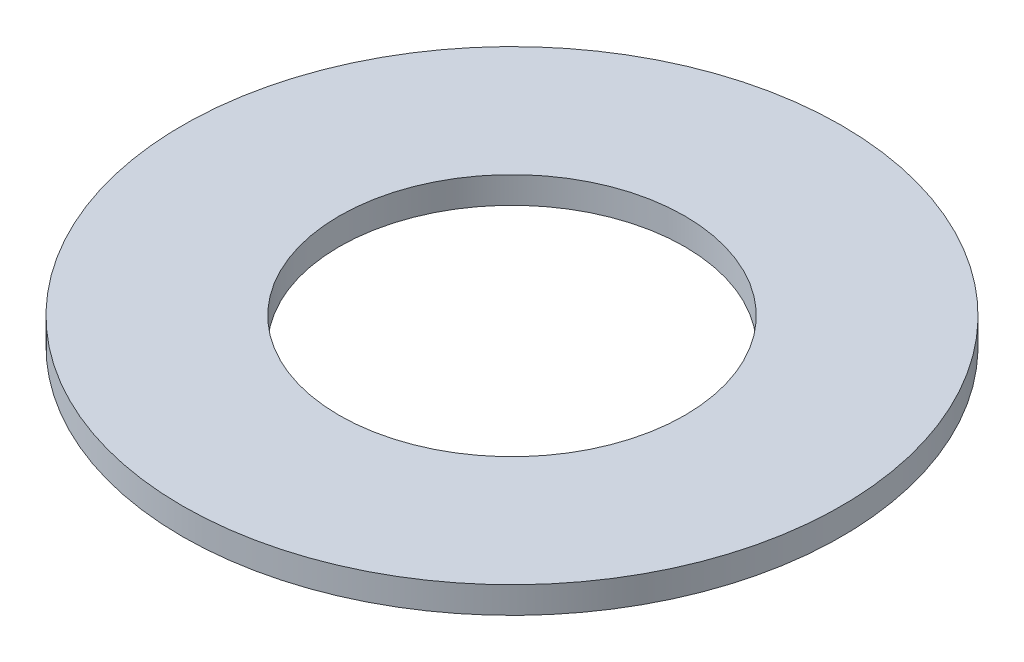
SolidWorks part; units mm, degrees
material "Polyetheretherketone (PEEK)"
ref_plane "Front Plane" through (0, 0, 0) normal (0, 0, 1) x (1, 0, 0)
ref_plane "Top Plane" through (0, 0, 0) normal (0, 1, 0) x (1, 0, 0)
ref_plane "Right Plane" through (0, 0, 0) normal (1, 0, 0) x (0, 0, -1)
sketch "Sketch1" plane through (0, 0, 0) normal (0, 1, 0) x (1, 0, 0)
  circle A0 centre (0, 0) radius 62
  dimension "D1" = 124
extrude "Boss-Extrude1" add sketch "Sketch1" along normal blind 5
sketch "Sketch2" plane through (0, 5, 0) normal (0, 1, 0) x (1, 0, 0)
  circle A0 centre (0, 49.5) radius 2
  dimension "D2" = 4
  dimension "D1" = 49.5
sketch "Sketch5" plane through (0, 0, 0) normal (0, -1, 0) x (1, 0, 0)
  circle A0 centre (0, 0) radius 32.5
  dimension "D1" = 65
extrude "Cut-Extrude2" cut sketch "Sketch5" against normal blind 10
